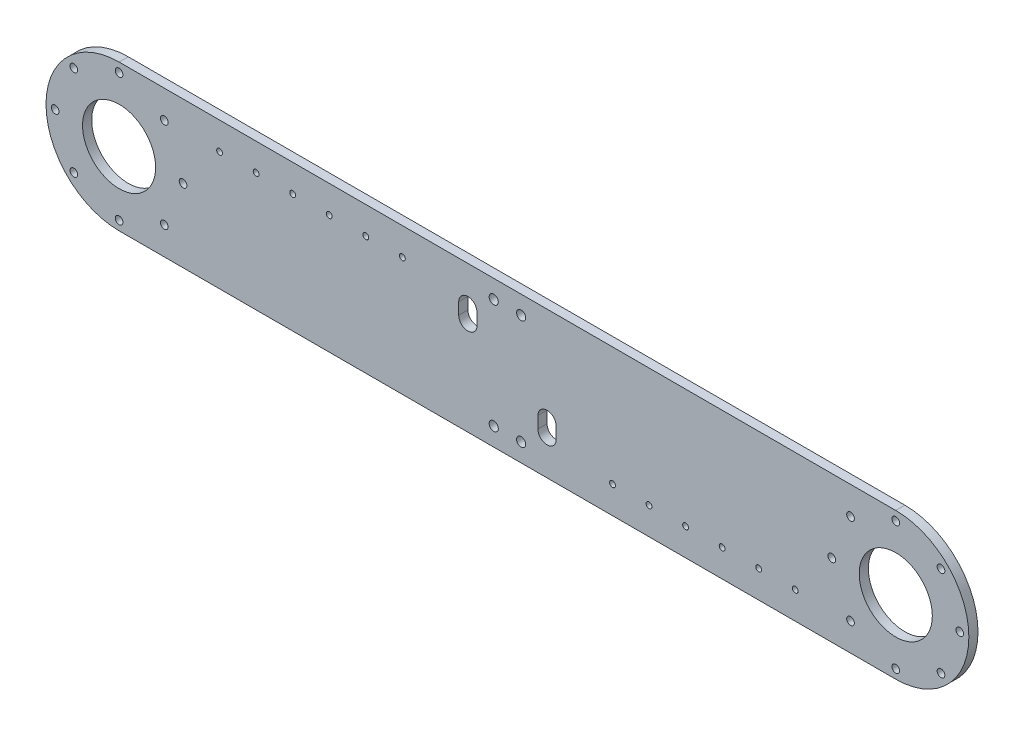
SolidWorks part; units mm, degrees
material "Thornel Mat VMA"
ref_plane "前视基准面" through (0, 0, 0) normal (0, 0, 1) x (1, 0, 0)
ref_plane "上视基准面" through (0, 0, 0) normal (0, 1, 0) x (1, 0, 0)
ref_plane "右视基准面" through (0, 0, 0) normal (1, 0, 0) x (0, 0, -1)
other "Configuration Table"
sketch "草图1" plane through (0, 0, 0) normal (0, 0, 1) x (1, 0, 0)
  line L0 (-212.5, 40) -> (212.5, 40)
  line L1 (-212.5, -40) -> (212.5, -40) construction
  line L2 (-212.5, -40) -> (-212.5, 40) construction
  line L3 (-212.5, 40) -> (212.5, 40) construction
  line L4 (212.5, -40) -> (212.5, 40) construction
  line L5 (0, 40) -> (0, -40) construction
  line L6 (-212.5, 0) -> (212.5, 0) construction
  line L7 (-212.5, -40) -> (212.5, -40)
  arc A0 (-212.5, 40) -> (-212.5, -40) centre (-212.5, 0) ccw
  arc A1 (212.5, -40) -> (212.5, 40) centre (212.5, 0) ccw
  point P0 (0, 0)
  dimension "D1" = 425
  dimension "D2" = 80
extrude "凸台-拉伸1" add sketch "草图1" along normal blind 5
sketch "草图2" plane through (0, 0, 5) normal (0, 0, 1) x (1, 0, 0)
  line L1 (-7.5, 30) -> (7.5, 30) construction
  line L2 (-7.5, 30) -> (-7.5, -30) construction
  line L3 (-7.5, -30) -> (7.5, -30) construction
  line L4 (7.5, 30) -> (7.5, -30) construction
  line L5 (0, -30) -> (0, 30) construction
  line L6 (-7.5, 0) -> (7.5, 0) construction
  circle A1 centre (-7.5, 30) radius 2.5
  circle A2 centre (7.5, 30) radius 2.5
  circle A3 centre (7.5, -30) radius 2.5
  circle A4 centre (-7.5, -30) radius 2.5
  point P0 (0, 0)
  dimension "D3" = 5
  dimension "D1" = 60
  dimension "D2" = 15
extrude "切除-拉伸1" cut sketch "草图2" against normal blind 10
sketch "草图3" plane through (0, 0, 5) normal (0, 0, 1) x (1, 0, 0)
  circle A0 centre (-212.5, 0) radius 20
  circle A1 centre (212.5, 0) radius 20
  dimension "D1" = 40
  dimension "D2" = 40
extrude "切除-拉伸2" cut sketch "草图3" against normal through all
sketch "草图4" plane through (0, 0, 0) normal (0, 0, -1) x (-1, 0, 0)
  line L0 (-21.6652, -12.9345) -> (-21.6652, -19.3184) construction
  line L1 (-16.6652, -12.9345) -> (-16.6652, -19.3184)
  line L2 (-26.6652, -12.9345) -> (-26.6652, -19.3184)
  line L3 (21.6652, 19.3184) -> (21.6652, 12.9345) construction
  line L4 (26.6652, 19.3184) -> (26.6652, 12.9345)
  line L5 (16.6652, 19.3184) -> (16.6652, 12.9345)
  arc A0 (-16.6652, -12.9345) -> (-26.6652, -12.9345) centre (-21.6652, -12.9345) ccw
  arc A1 (-26.6652, -19.3184) -> (-16.6652, -19.3184) centre (-21.6652, -19.3184) ccw
  arc A2 (26.6652, 19.3184) -> (16.6652, 19.3184) centre (21.6652, 19.3184) ccw
  arc A3 (16.6652, 12.9345) -> (26.6652, 12.9345) centre (21.6652, 12.9345) ccw
  point P4 (-21.6652, -16.1264)
  point P13 (21.6652, 16.1264)
  dimension "D1" = 5
  dimension "D2" = 5
extrude "切除-拉伸3" cut sketch "草图4" against normal through all
sketch "草图5" plane through (0, 0, 5) normal (0, 0, 1) x (1, 0, 0)
  line L0 (42.5, -25) -> (172.5, -25) construction
  line L1 (-212.5, -40) -> (212.5, -40) construction
  line L2 (-172.5, 25) -> (-42.5, 25) construction
  line L3 (212.5, 40) -> (-212.5, 40) construction
  circle A0 centre (212.5, 0) radius 20 construction
  circle A1 centre (57.5, -25) radius 1.6
  circle A2 centre (77.5, -25) radius 1.6
  circle A3 centre (97.5, -25) radius 1.6
  circle A4 centre (117.5, -25) radius 1.6
  circle A5 centre (137.5, -25) radius 1.6
  circle A6 centre (157.5, -25) radius 1.6
  circle A7 centre (-212.5, 0) radius 20 construction
  circle A8 centre (-57.5, 25) radius 1.6
  circle A9 centre (-77.5, 25) radius 1.6
  circle A10 centre (-97.5, 25) radius 1.6
  circle A11 centre (-117.5, 25) radius 1.6
  circle A12 centre (-137.5, 25) radius 1.6
  circle A13 centre (-157.5, 25) radius 1.6
  dimension "D4" = 3.2
  dimension "D11" = 3.2
  dimension "D1" = 15
  dimension "D2" = 130
  dimension "D3" = 40
  dimension "D5" = 15
  dimension "D7" = 20
  dimension "D8" = 130
  dimension "D9" = 15
  dimension "D10" = 40
  dimension "D12" = 15
  dimension "D14" = 20
  dimension "D6" = 6
  dimension "D13" = 6
extrude "切除-拉伸4" cut sketch "草图5" against normal through all
sketch "草图6" plane through (0, 0, 0) normal (0, 0, -1) x (-1, 0, 0)
  circle A0 centre (-212.5, 0) radius 35 construction
  circle A1 centre (-247.5, 0) radius 2.1
  circle A2 centre (-237.2487, 24.7487) radius 2.1
  circle A3 centre (-212.5, 35) radius 2.1
  circle A4 centre (-187.7513, 24.7487) radius 2.1
  circle A5 centre (-177.5, 0) radius 2.1
  circle A6 centre (-187.7513, -24.7487) radius 2.1
  circle A7 centre (-212.5, -35) radius 2.1
  circle A8 centre (-237.2487, -24.7487) radius 2.1
  point P21 (-212.5, 0)
  dimension "D1" = 70
  dimension "D2" = 4.2
  dimension "D3" = 8
extrude "切除-拉伸5" cut sketch "草图6" against normal through all
mirror "镜向1" about plane through (0, 0, 0) normal (1, 0, 0) of "切除-拉伸5"
